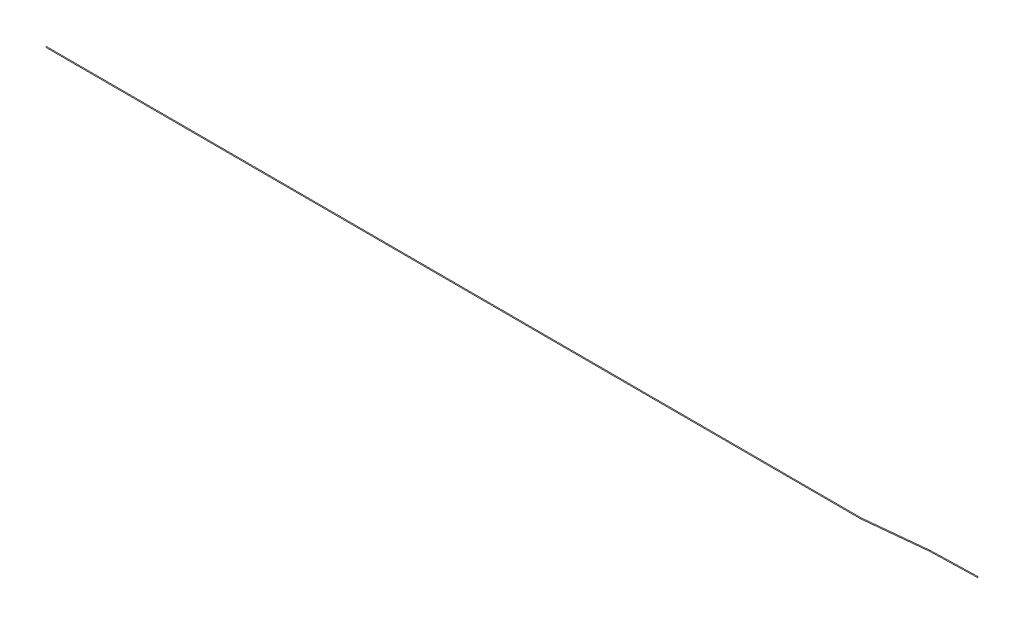
SolidWorks part; units mm, degrees
material "Nickel"
ref_plane "Front Plane" through (0, 0, 0) normal (0, 0, 1) x (1, 0, 0)
ref_plane "Top Plane" through (0, 0, 0) normal (0, 1, 0) x (1, 0, 0)
ref_plane "Right Plane" through (0, 0, 0) normal (1, 0, 0) x (0, 0, -1)
sketch3d "3DSketch1"
  line L0 (-275.6019, 9.6145, -32.2799) -> (386.9953, 7.8526, -33.308)
  line L1 (437.5124, 7.5872, -38.7393) -> (386.9953, 7.8526, -33.308)
  line L2 (437.5124, 7.5872, -38.7393) -> (476.2969, 8.3143, -39.0392)
sweep "Sweep1" add path "3DSketch1" circular profile diameter 0.65 parameters "D3"=0.65
